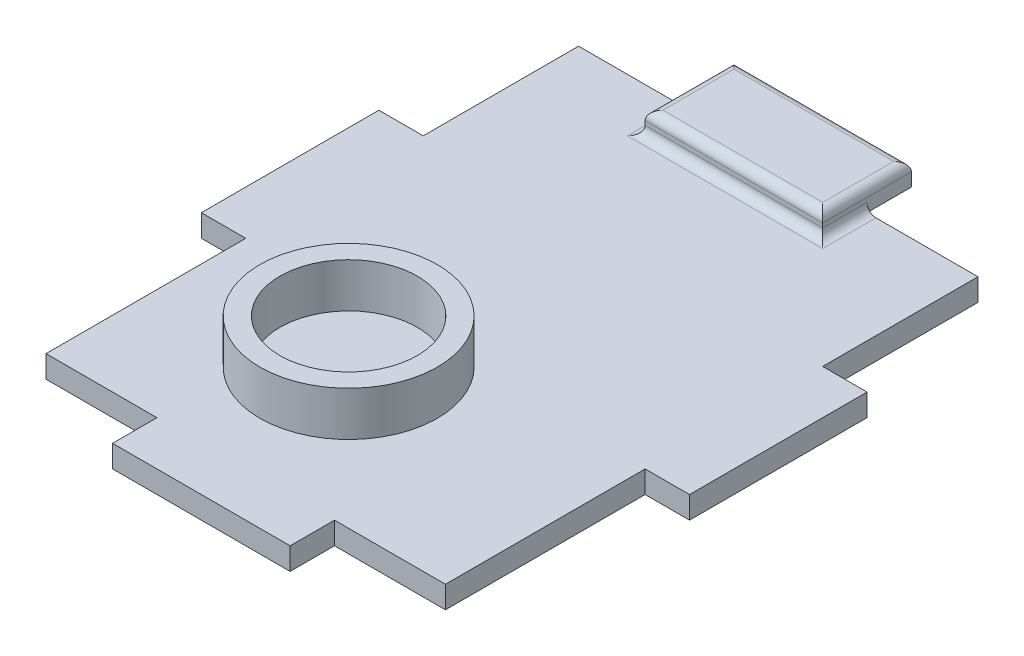
SolidWorks part; units mm, degrees
ref_plane "Front Plane" through (0, 0, 0) normal (0, 0, 1) x (1, 0, 0)
ref_plane "Top Plane" through (0, 0, 0) normal (0, 1, 0) x (1, 0, 0)
ref_plane "Right Plane" through (0, 0, 0) normal (1, 0, 0) x (0, 0, -1)
sketch "Sketch1" plane through (0, 0, 0) normal (0, 1, 0) x (1, 0, 0)
  line L1 (0, 0) -> (90, 0)
  line L2 (0, 0) -> (0, 120)
  line L3 (0, 120) -> (90, 120)
  line L4 (90, 0) -> (90, 120)
  line L5 (0, 85) -> (-10, 85)
  line L6 (0, 85) -> (0, 45)
  line L7 (0, 45) -> (-10, 45)
  line L8 (-10, 85) -> (-10, 45)
  line L9 (25, 120) -> (65, 120)
  line L13 (90, 85) -> (100, 85)
  line L14 (90, 85) -> (90, 45)
  line L15 (90, 45) -> (100, 45)
  line L16 (100, 85) -> (100, 45)
  line L17 (65, 0) -> (25, 0)
  line L18 (65, 0) -> (65, -10)
  line L19 (65, -10) -> (25, -10)
  line L20 (25, 0) -> (25, -10)
  point P10 (0, 0)
  point P11 (0, 0)
  point P23 (45, 0)
  point P24 (45, 120)
  dimension "D1" = 90
  dimension "D2" = 120
  dimension "D3" = 10
  dimension "D5" = 10
  dimension "D6" = 10
  dimension "D8" = 40
  dimension "D9" = 40
  dimension "D10" = 40
  dimension "D11" = 45
  dimension "D12" = 45
extrude "Boss-Extrude1" add sketch "Sketch1" along normal blind 5 contours L1 L4 L3 L2 | L5 L8 L7 L2 | L16 L13 L4 L15 | L1 L20 L19 L18
sketch "Sketch4" plane through (0, 5, 0) normal (0, 1, 0) x (1, 0, 0)
  line L0 (0, 0) -> (0, 45) construction
  line L1 (65, 0) -> (90, 0) construction
  circle A0 centre (36.72, 31.47) radius 31.25
  circle A1 centre (36.72, 31.47) radius 15.5
  circle A2 centre (36.72, 31.47) radius 20
  dimension "D3" = 62.5
  dimension "D4" = 31
  dimension "D5" = 40
  dimension "D1" = 36.72
  dimension "D2" = 31.47
extrude "Boss-Extrude2" add sketch "Sketch4" along normal blind 10 contours A2 A1
sketch "Sketch5" plane through (0, 5, 0) normal (0, 1, 0) x (1, 0, 0)
  line L0 (0, 120) -> (90, 120) construction
  line L1 (65, 130) -> (25, 130)
  line L2 (65, 130) -> (65, 110)
  line L3 (65, 110) -> (25, 110)
  line L4 (25, 130) -> (25, 110)
  line L5 (65, 130) -> (25, 110) construction
  line L6 (65, 110) -> (25, 130) construction
  point P0 (45, 120)
  dimension "D1" = 20
  dimension "D2" = 40
extrude "Boss-Extrude3" add sketch "Sketch5" along normal blind 5
fillet "Fillet1" radius 2 7 edges at (25, 5, -115) (45, 5, -110) (65, 5, -115) (25, 10, -120) (45, 10, -110) (65, 10, -120) (45, 10, -130)
equation "\"D4@Sketch4\"=15.5*2"
